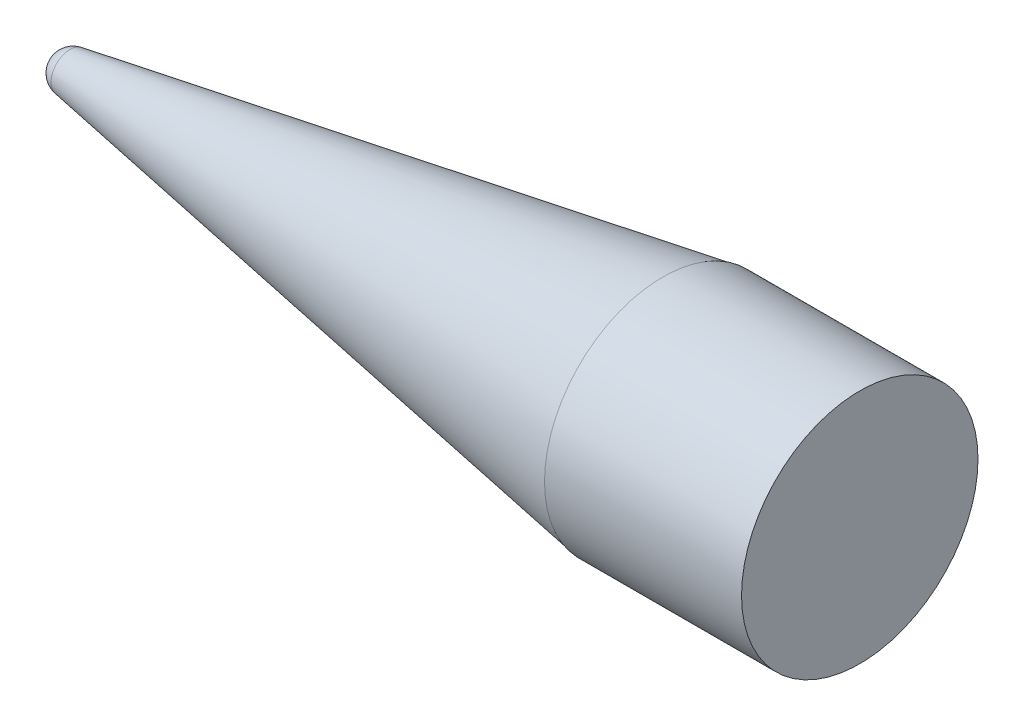
SolidWorks part; units mm, degrees
ref_plane "Front Plane" through (0, 0, 0) normal (0, 0, 1) x (1, 0, 0)
ref_plane "Top Plane" through (0, 0, 0) normal (0, 1, 0) x (1, 0, 0)
ref_plane "Right Plane" through (0, 0, 0) normal (1, 0, 0) x (0, 0, -1)
sketch "Sketch1" plane through (0, 0, 0) normal (0, 1, 0) x (1, 0, 0)
  line L0 (0, 0) -> (457.2564, 0) construction
  line L1 (457.2564, 75.8614) -> (457.2564, 0)
  line L2 (64.8943, 0) -> (457.2564, 0)
  arc A0 (75.2196, 12.1886) -> (64.8943, 0) centre (77.2511, 0) ccw
  spline S0 degree 1 poles (0.0564, -0.3386) (457.2564, 75.8614) knots 0 0 1 1 construction
  spline S1 degree 1 poles (75.2196, 12.1886) (457.2564, 75.8614) knots 0.164399 0.164399 1 1
  point P1 (0, 0)
  point P9 (0, 0)
  point P11 (0, 0)
revolve "Revolve3" add sketch "Sketch1" angle 360 about L0
sketch "Sketch2" plane through (457.2564, 0, 0) normal (1, 0, 0) x (0, 0, -1)
  circle A0 centre (0, 0) radius 76.2
extrude "Boss-Extrude1" add sketch "Sketch2" along normal blind 127
